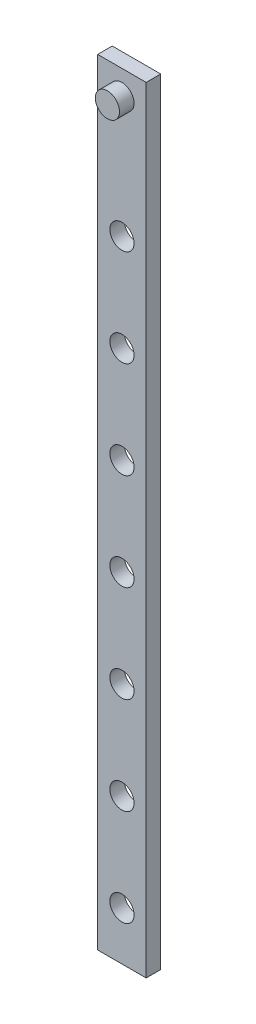
SolidWorks part; units mm, degrees
ref_plane "前基準面" through (0, 0, 0) normal (0, 0, 1) x (1, 0, 0)
ref_plane "上基準面" through (0, 0, 0) normal (0, 1, 0) x (1, 0, 0)
ref_plane "右基準面" through (0, 0, 0) normal (1, 0, 0) x (0, 0, -1)
sketch "草圖1" plane through (0, 0, 0) normal (0, 0, 1) x (1, 0, 0)
  line L0 (0, -80) -> (0, 80) construction
  line L1 (-5, -80) -> (5, -80)
  line L2 (-5, -80) -> (-5, 80)
  line L3 (-5, 80) -> (5, 80)
  line L4 (5, -80) -> (5, 80)
  line L5 (-5, -80) -> (5, 80) construction
  line L6 (-5, 80) -> (5, -80) construction
  circle A0 centre (0, -70) radius 2.5
  circle A1 centre (0, -50) radius 2.5
  circle A2 centre (0, -30) radius 2.5
  circle A3 centre (0, -10) radius 2.5
  circle A4 centre (0, 10) radius 2.5
  circle A5 centre (0, 30) radius 2.5
  circle A6 centre (0, 50) radius 2.5
  point P0 (0, 0)
  dimension "D3" = 10
  dimension "D9" = 5
  dimension "D11" = 5
  dimension "D1" = 160
  dimension "D2" = 10
  dimension "D4" = 20
  dimension "D5" = 20
  dimension "D6" = 20
  dimension "D7" = 20
  dimension "D8" = 20
  dimension "D10" = 20
extrude "填料-伸長1" add sketch "草圖1" along normal blind 3
sketch "草圖2" plane through (0, 0, 3) normal (0, 0, 1) x (1, 0, 0)
  line L1 (5, 80) -> (-5, 80) construction
  circle A0 centre (0, 75) radius 2.5
  dimension "D1" = 5
  dimension "D2" = 5
extrude "填料-伸長2" add sketch "草圖2" along normal blind 3
